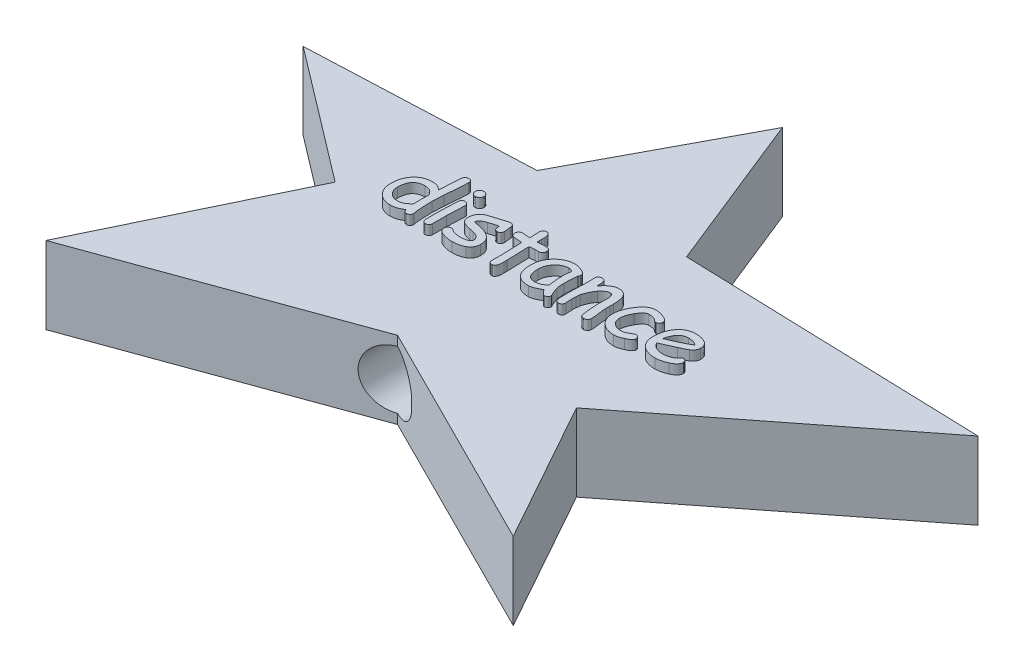
SolidWorks part; units mm, degrees
ref_plane "Front Plane" through (0, 0, 0) normal (0, 0, 1) x (1, 0, 0)
ref_plane "Top Plane" through (0, 0, 0) normal (0, 1, 0) x (1, 0, 0)
ref_plane "Right Plane" through (0, 0, 0) normal (1, 0, 0) x (0, 0, -1)
sketch "Sketch1" plane through (0, 0, 0) normal (0, 1, 0) x (1, 0, 0)
  line L0 (0, 0) -> (6.6336, -16.5533)
  line L1 (6.6336, -16.5533) -> (37.7799, -17.5362)
  line L2 (37.7799, -17.5362) -> (14.475, -35.7939)
  line L3 (14.475, -35.7939) -> (22.7175, -50.5804)
  line L4 (22.7175, -50.5804) -> (-1.2915, -38.5441)
  line L5 (-1.2915, -38.5441) -> (-27.9879, -48.2391)
  line L6 (-27.9879, -48.2391) -> (-18.2522, -28.044)
  line L7 (-18.2522, -28.044) -> (-32.0701, -17.5362)
  line L9 (-32.0701, -17.5362) -> (-8.8376, -16.5533)
  line L10 (-8.8376, -16.5533) -> (0, 0)
  point P3 (-37.758, -18.3318)
  point P11 (11.1121, -16.5533)
  point P13 (21.969, -56.2902)
  point P14 (14.5049, -38.2405)
  point P15 (23.5976, -61.8544)
  point P16 (15.9977, -37.1548)
  point P17 (39.0688, -11.3695)
  point P18 (-8.8376, -16.5533)
  point P19 (-37.3371, -18.6979)
  point P20 (-14.9447, -27.2478)
  point P21 (9.2121, -20.055)
  point P22 (38.933, -15.4408)
  point P23 (-17.2391, -30.1137)
  point P24 (7.9907, -2.2768)
  point P25 (-8.8376, -32.4048)
  point P26 (-10.6019, -28.1978)
  point P27 (-11.2804, -34.7119)
  point P28 (0, 0)
  point P29 (-12.3661, -31.862)
  point P30 (0, 0)
  point P31 (0, 0)
  point P32 (-11.8233, -33.6262)
  point P33 (0, 0)
  point P34 (-12.0947, -32.4048)
  point P35 (22.5119, -55.3402)
  point P36 (6.6336, -16.5533)
  point P37 (-11.2804, -30.6406)
  point P38 (14.475, -35.7939)
  point P39 (-36.4273, -16.5533)
  point P40 (-12.874, -31.0836)
  point P41 (0, 0)
  point P42 (22.7175, -50.5804)
  point P43 (-27.9879, -48.2391)
  point P44 (-1.2915, -38.5441)
  point P45 (28.9866, -17.4532)
  point P46 (39.0345, -16.5533)
  point P47 (-18.2522, -28.044)
  point P48 (0, 0)
  point P49 (-32.0701, -17.5362)
extrude "Boss-Extrude1" add sketch "Sketch1" along normal blind 8 contours L5 L6 L7 L9 L10 L0 L1 L2 L3 L4
sketch "Sketch2" plane through (0, 8, 0) normal (0, 1, 0) x (1, 0, 0)
  text T0 "distance\r\n" font "Comic Sans MS" height 6
extrude "Boss-Extrude2" add sketch "Sketch2" along normal blind 1
ref_plane "Plane1" through (0, 0, 40) normal (0, 0, 1) x (1, 0, 0)
sketch "Sketch4" plane through (0, 0, 40) normal (0, 0, 1) x (1, 0, 0)
  line L0 (-1.2915, 8) -> (-1.2915, 0) construction
  circle A0 centre (-1.2915, 4) radius 3
  dimension "D1" = 6
extrude "Cut-Extrude2" cut sketch "Sketch4" against normal blind 6
